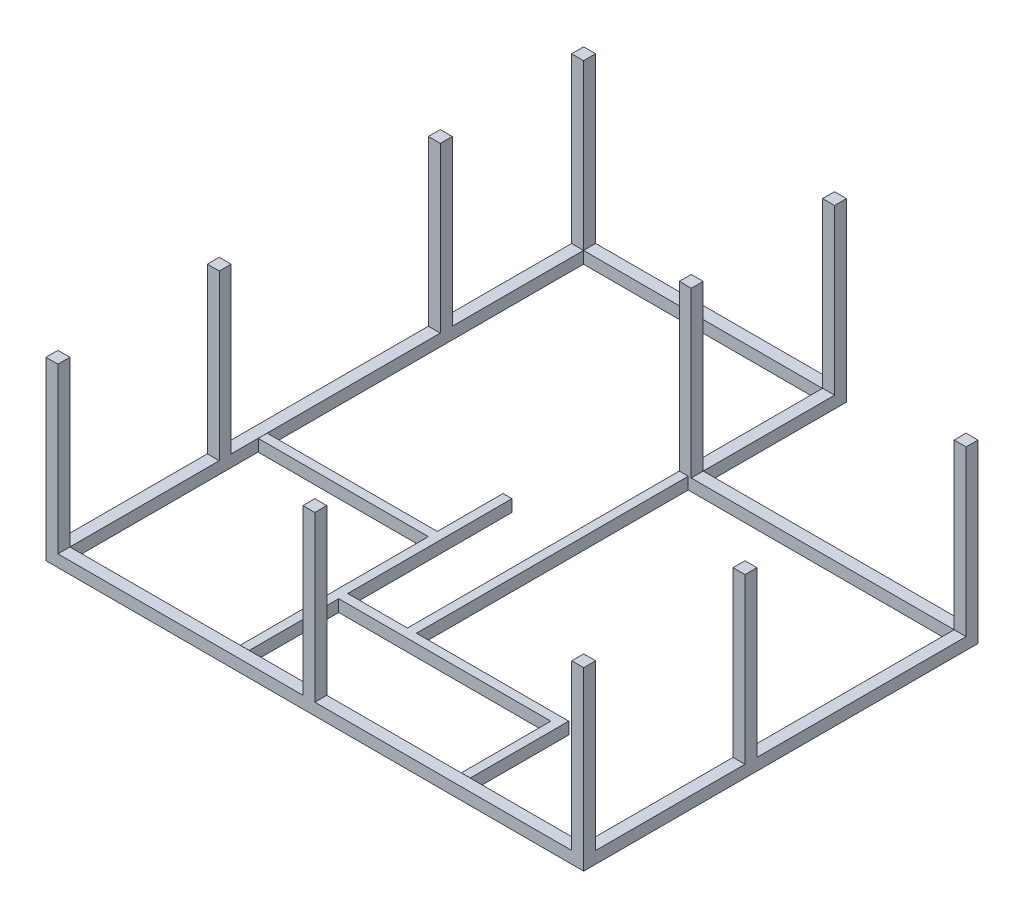
SolidWorks part; units mm, degrees
ref_plane "Спереди" through (0, 0, 0) normal (0, 0, 1) x (1, 0, 0)
ref_plane "Сверху" through (0, 0, 0) normal (0, 1, 0) x (1, 0, 0)
ref_plane "Справа" through (0, 0, 0) normal (1, 0, 0) x (0, 0, -1)
sketch "Эскиз1" plane through (0, 0, 0) normal (0, 1, 0) x (-1, 0, 0)
  line L0 (0, 0) -> (-9000, 0)
  line L1 (-9000, 0) -> (-9000, -6600)
  line L2 (-9000, -6600) -> (-4400, -6600)
  line L4 (-4400, -6600) -> (-4400, -9000)
  line L5 (-4400, -9000) -> (0, -9000)
  line L6 (0, -9000) -> (0, 0)
  line L7 (-200, -200) -> (-8800, -200)
  line L8 (-4350, -6400) -> (-4350, -1850)
  line L10 (-4200, -8797) -> (-200, -8797)
  line L11 (-200, -8797) -> (-200, -200)
  line L12 (-8800, -200) -> (-8800, -6400)
  line L13 (-4350, -1850) -> (-6900, -1850)
  line L15 (-6900, -1850) -> (-6900, -203)
  line L20 (-6900, -203) -> (-6750, -203)
  line L22 (-4350, -6400) -> (-8800, -6400)
  line L23 (-4500, -200) -> (-8800, -200) construction
  line L24 (-8800, -203) -> (-8800, -2700) construction
  line L25 (-8797, -6600) -> (-4400, -6600) construction
  line L26 (-8797, -6400) -> (-4400, -6400) construction
  line L27 (-4400, -6600) -> (-9000, -6600) construction
  line L28 (-4400, -8797) -> (-4400, -6603) construction
  line L32 (-4200, -8797) -> (-4200, -6603) construction
  line L33 (-6750, -203) -> (-6750, -1700)
  line L34 (0, -9000) -> (-4400, -9000) construction
  line L35 (-3597.5552, -8797) -> (-2379.0159, -8797) construction
  line L36 (-6750, -1700) -> (-3200, -1700)
  line L37 (-3200, -1700) -> (-3200, -203)
  line L38 (-3200, -203) -> (-3050, -203)
  line L39 (-3050, -203) -> (-3050, -3350)
  line L40 (-3050, -3350) -> (-203, -3350)
  line L41 (-203, -3350) -> (-203, -3500)
  line L42 (-203, -3500) -> (-3050, -3500)
  line L43 (-3050, -3500) -> (-3050, -4600)
  line L44 (-3050, -4600) -> (-3200, -4600)
  line L45 (-3200, -4600) -> (-3200, -1850)
  line L46 (-3200, -1850) -> (-4200, -1850)
  line L47 (-4200, -1850) -> (-4200, -8797)
  dimension "D1" = 200
  dimension "D2" = 200
  dimension "D3" = 200
extrude "Бобышка-Вытянуть1" add sketch "Эскиз1" against normal blind 200
sketch "Эскиз2" plane through (0, -200, 0) normal (0, 1, 0) x (1, 0, 0)
  line L0 (9000, 0) -> (9000, 6600) construction
  line L1 (0, 9000) -> (200, 9000)
  line L2 (0, 9000) -> (0, 8797)
  line L3 (0, 8797) -> (200, 8797)
  line L4 (200, 9000) -> (200, 8797)
  line L5 (9000, 2900) -> (8800, 2900)
  line L6 (9000, 2900) -> (9000, 2700)
  line L7 (200, 200) -> (8800, 200) construction
  line L8 (4200, 9000) -> (4400, 9000)
  line L9 (4200, 9000) -> (4200, 8800)
  line L10 (4200, 8800) -> (4400, 8800)
  line L11 (4400, 9000) -> (4400, 8800)
  line L12 (4400, 6600) -> (4200, 6600)
  line L13 (4400, 6600) -> (4400, 6400)
  line L14 (4400, 6400) -> (4200, 6400)
  line L15 (4200, 6600) -> (4200, 6400)
  line L16 (9000, 2700) -> (8800, 2700)
  line L17 (4350, 6400) -> (8800, 6400) construction
  line L18 (8800, 2900) -> (8800, 2700)
  line L19 (4300, 200) -> (4500, 200)
  line L20 (9000, 6600) -> (8800, 6600)
  line L21 (9000, 6600) -> (9000, 6400)
  line L22 (9000, 6400) -> (8800, 6400)
  line L23 (8800, 6600) -> (8800, 6400)
  line L24 (9000, 0) -> (8800, 0)
  line L25 (9000, 0) -> (9000, 200)
  line L26 (9000, 200) -> (8800, 200)
  line L27 (8800, 0) -> (8800, 200)
  line L28 (0, 0) -> (200, 0)
  line L29 (0, 0) -> (0, 200)
  line L30 (0, 200) -> (200, 200)
  line L31 (200, 0) -> (200, 200)
  line L36 (4300, 200) -> (4300, 0)
  line L37 (4300, 0) -> (4500, 0)
  line L38 (8800, 2900) -> (9000, 2900) construction
  line L39 (4500, 200) -> (4500, 0)
  line L40 (8800, 200) -> (8800, 6400) construction
  line L41 (8800, 2700) -> (9000, 2700) construction
  line L42 (0, 9000) -> (0, 0) construction
  line L43 (0, 2900) -> (200, 2900)
  line L44 (0, 2900) -> (0, 2700)
  line L45 (0, 2700) -> (200, 2700)
  line L46 (200, 2900) -> (200, 2700)
  line L47 (0, 0) -> (0, 9000) construction
  line L48 (200, 8797) -> (200, 200) construction
  line L49 (0, 2700) -> (200, 2700) construction
  line L50 (4400, 6600) -> (4400, 9000) construction
  line L51 (4400, 9000) -> (0, 9000) construction
  line L52 (4200, 1850) -> (4200, 8797) construction
  line L53 (200, 8797) -> (200, 200) construction
  line L54 (200, 6600) -> (0, 6600)
  line L55 (200, 6600) -> (200, 6400)
  line L56 (200, 6400) -> (0, 6400)
  line L57 (0, 6600) -> (0, 6400)
  line L58 (0, 6600) -> (200, 6600) construction
  line L59 (0, 9000) -> (0, 0) construction
  line L60 (0, 6400) -> (200, 6400) construction
  line L61 (4300, 0) -> (4300, 200) construction
  line L62 (0, 0) -> (9000, 0) construction
  dimension "D1" = 200
extrude "Бобышка-Вытянуть2" add sketch "Эскиз2" along normal up to surface (2950 mm away)
